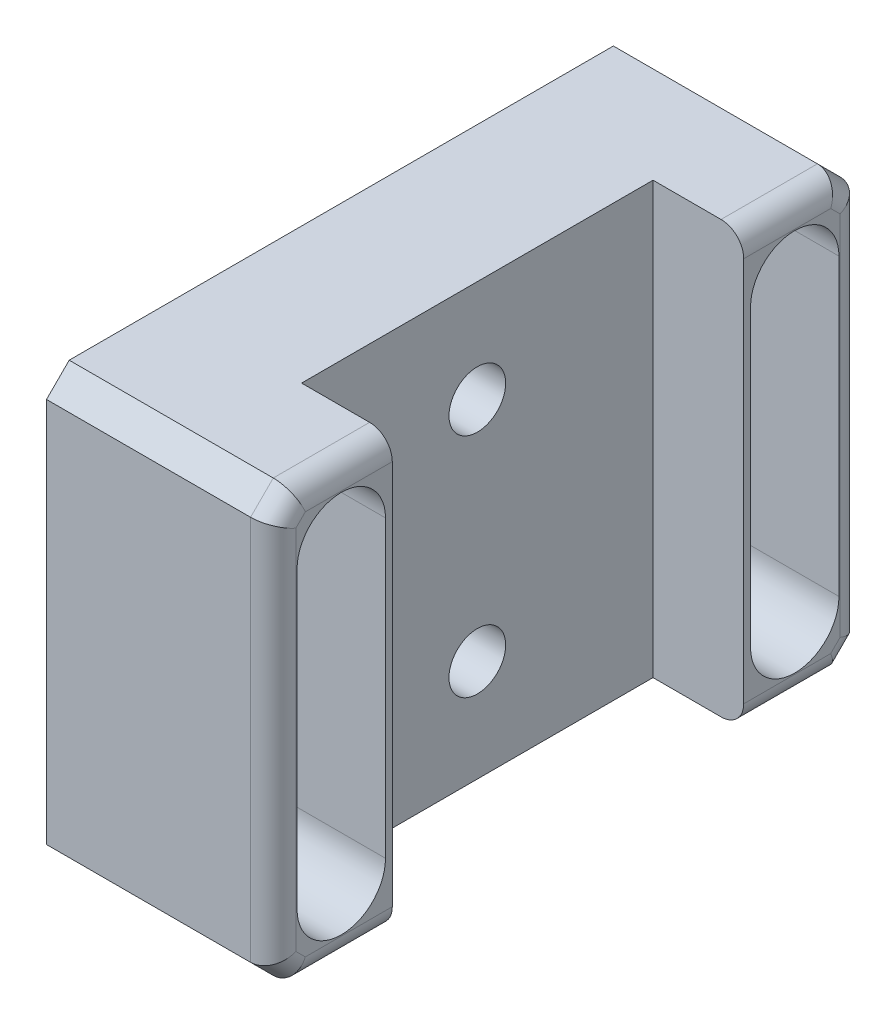
SolidWorks part; units mm, degrees
ref_plane "Спереди" through (0, 0, 0) normal (0, 0, 1) x (1, 0, 0)
ref_plane "Сверху" through (0, 0, 0) normal (0, 1, 0) x (1, 0, 0)
ref_plane "Справа" through (0, 0, 0) normal (1, 0, 0) x (0, 0, -1)
sketch "Эскиз1" plane through (0, 0, 0) normal (1, 0, 0) x (0, 0, -1)
  line L0 (-10, 6.5) -> (-10, -6.5) construction
  line L1 (-13, 9.5) -> (13, 9.5)
  line L2 (-13, 9.5) -> (-13, -9.5)
  line L3 (-13, -9.5) -> (13, -9.5)
  line L4 (13, 9.5) -> (13, -9.5)
  line L5 (-13, 9.5) -> (13, -9.5) construction
  line L6 (-13, -9.5) -> (13, 9.5) construction
  line L7 (-8.75, 6.5) -> (-8.75, -6.5)
  line L8 (-11.25, 6.5) -> (-11.25, -6.5)
  line L9 (0, 9.5) -> (0, -9.5) construction
  line L10 (10, 6.5) -> (10, -6.5) construction
  line L11 (8.75, 6.5) -> (8.75, -6.5)
  line L12 (11.25, 6.5) -> (11.25, -6.5)
  arc A0 (-8.75, 6.5) -> (-11.25, 6.5) centre (-10, 6.5) ccw
  arc A1 (-11.25, -6.5) -> (-8.75, -6.5) centre (-10, -6.5) ccw
  arc A2 (8.75, 6.5) -> (11.25, 6.5) centre (10, 6.5) cw
  arc A3 (11.25, -6.5) -> (8.75, -6.5) centre (10, -6.5) cw
  point P0 (0, 0)
  point P8 (-10, 0)
  point P17 (10, 0)
  dimension "D1" = 26
  dimension "D2" = 2.5
  dimension "D3" = 20
  dimension "D5" = 3
  dimension "D4" = 19
extrude "Бобышка-Вытянуть1" add sketch "Эскиз1" along normal blind 10
sketch "Эскиз2" plane through (10, 0, 0) normal (1, 0, 0) x (0, 0, -1)
  line L0 (-13, -9.5) -> (13, -9.5) construction
  line L1 (7.75, 9.5) -> (-7.75, 9.5)
  line L2 (7.75, 9.5) -> (7.75, -9.5)
  line L3 (7.75, -9.5) -> (-7.75, -9.5)
  line L4 (-7.75, 9.5) -> (-7.75, -9.5)
  line L5 (7.75, 9.5) -> (-7.75, -9.5) construction
  line L6 (7.75, -9.5) -> (-7.75, 9.5) construction
  point P0 (0, 0)
  dimension "D1" = 15.5
extrude "Вырез-Вытянуть1" cut sketch "Эскиз2" against normal blind 4
sketch "Эскиз3" plane through (10, 0, 0) normal (1, 0, 0) x (0, 0, -1)
  line L0 (-10, -6.5) -> (-10, 6.5) construction
  line L1 (-11.95, -6.5) -> (-11.95, 6.5)
  line L2 (-8.05, -6.5) -> (-8.05, 6.5)
  line L3 (0, 9.5) -> (0, -9.5) construction
  line L4 (7.75, 9.5) -> (-7.75, 9.5) construction
  line L5 (-7.75, -9.5) -> (7.75, -9.5) construction
  line L6 (10, -6.5) -> (10, 6.5) construction
  line L7 (11.95, -6.5) -> (11.95, 6.5)
  line L8 (8.05, -6.5) -> (8.05, 6.5)
  arc A0 (-11.95, -6.5) -> (-8.05, -6.5) centre (-10, -6.5) ccw
  arc A1 (-8.05, 6.5) -> (-11.95, 6.5) centre (-10, 6.5) ccw
  arc A2 (-11.25, -6.5) -> (-8.75, -6.5) centre (-10, -6.5) ccw construction
  arc A3 (-8.75, 6.5) -> (-11.25, 6.5) centre (-10, 6.5) ccw construction
  arc A4 (11.95, -6.5) -> (8.05, -6.5) centre (10, -6.5) cw
  arc A5 (8.05, 6.5) -> (11.95, 6.5) centre (10, 6.5) cw
  point P2 (-10, 0)
  point P23 (10, 0)
  dimension "D1" = 3.9
extrude "Вырез-Вытянуть2" cut sketch "Эскиз3" against normal blind 4
chamfer "Фаска1" distance 1 angle 45 4 edges at (5, 9.5, -13) (5, -9.5, -13) (5, -9.5, 13) (5, 9.5, 13)
fillet "Скругление1" radius 1 10 edges at (10, 9, 12.5) (10, -9, 12.5) (10, -9, -12.5) (10, -9.5, -9.875) (10, 0, -13) (10, 9, -12.5) (10, 9.5, -9.875) (10, -9.5, 9.875) (10, 9.5, 9.875) (10, 0, 13)
sketch "Эскиз4" plane through (6, 0, 0) normal (1, 0, 0) x (0, 0, -1)
  line L0 (0, 9.5) -> (0, -9.5) construction
  line L1 (7.75, 9.5) -> (-7.75, 9.5) construction
  line L2 (-7.75, -9.5) -> (7.75, -9.5) construction
  line L3 (-7.75, 0) -> (7.75, 0) construction
  line L4 (-7.75, 9.5) -> (-7.75, -9.5) construction
  line L5 (7.75, -9.5) -> (7.75, 9.5) construction
  circle A0 centre (0, 5) radius 1.25
  circle A1 centre (0, -5) radius 1.25
  dimension "D1" = 2.5
  dimension "D2" = 10
extrude "Вырез-Вытянуть3" cut sketch "Эскиз4" against normal through all
sketch "Эскиз5" plane through (0, 0, 0) normal (-1, 0, 0) x (0, 0, 1)
  line L1 (1.1691, 2.975) -> (2.3383, 5)
  line L2 (2.3383, 5) -> (1.1691, 7.025)
  line L3 (1.1691, 7.025) -> (-1.1691, 7.025)
  line L4 (-1.1691, 7.025) -> (-2.3383, 5)
  line L5 (-2.3383, 5) -> (-1.1691, 2.975)
  line L6 (-1.1691, 2.975) -> (1.1691, 2.975)
  line L7 (1.1691, -7.025) -> (2.3383, -5)
  line L8 (2.3383, -5) -> (1.1691, -2.975)
  line L9 (1.1691, -2.975) -> (-1.1691, -2.975)
  line L10 (-1.1691, -2.975) -> (-2.3383, -5)
  line L11 (-2.3383, -5) -> (-1.1691, -7.025)
  line L12 (-1.1691, -7.025) -> (1.1691, -7.025)
  circle A0 centre (0, 5) radius 2.025 construction
  circle A1 centre (0, -5) radius 2.025 construction
  dimension "D1" = 4.05
  dimension "D2" = 4.05
extrude "Вырез-Вытянуть4" cut sketch "Эскиз5" against normal blind 2
equation "\"motor_diameter\"= 30"
equation "\"mm_diameter\"= IIF ( \"motor_diameter\" < 34 , 41 , \"motor_diameter\" + 8 )"
equation "\"upper_shafts_diameter\"= 5"
equation "\"upper_shats_length\"= 180"
equation "\"upper_bearing_d1\"= 10"
equation "\"upper_bearing_d2\"= 5"
equation "\"upper_bearing_h\"= 15"
equation "\"lower_shafts_diameter\"= 5"
equation "\"lower_shafts_length\"= 180"
equation "\"lower_bearing_d1\"= 10"
equation "\"lower_bearing_d2\"= 5"
equation "\"lower_bearing_h\"= 15"
equation "\"print_offset\"= 0.5"
equation "\"bh_screws_d\"= 2"
equation "\"bh_screws_h\"= 20"
equation "\"bh_screws_hh_d\"= 3.4"
equation "\"bh_screws_hh_h\"= 2"
equation "\"bh_nut_d\"= 3.8"
equation "\"bh_nut_h\"= 2"
equation "\"motor_screws_d\"= 3"
equation "\"motor_screws_h\"= 16"
equation "\"motor_screws_hh_d\"= 5.5"
equation "\"motor_screws_hh_h\"= 3"
equation "\"plate_hole_distance\"= 25.4"
equation "\"plate_screws_d\"= 6.5"
equation "\"shafts_diameter\"= IIF ( \"mm_diameter\" < 42 , 42 + 8 , \"mm_diameter\" + 8 )"
equation "\"central_hole_diameter\"= 8"
equation "\"bh_thikness\"= 4"
equation "\"ends_screws_d\"= 4"
equation "\"ends_screws_h\"= 16"
equation "\"ends_screws_hh_d\"= 6.7"
equation "\"ends_screws_hh_h\"= 4.1"
equation "\"ends_nut_d\"= 6.8"
equation "\"ends_nut_h\"= 3"
equation "\"system_radius\" = ( \"shafts_diameter\" + 12 + \"bh_thikness\" / 2 ) / 2"
equation "\"encoder_distance\"= \"system_radius\" + 4"
equation "\"tape_position\"= \"encoder_distance\" - 2 + 3.9 + 1.7 / 2"
equation "\"D2@Эскиз1\"=\"bh_screws_d\"+\"print_offset\""
equation "\"D1@Бобышка-Вытянуть1\"=6"
equation "\"D4@Эскиз1\"=\"upper_bearing_h\" + 6 + 3 - 8 + 3"
equation "\"D1@Эскиз2\"=\"print_offset\"+15"
equation "\"D1@Эскиз3\"=\"bh_screws_hh_d\"+\"print_offset\""
equation "\"D1@Вырез-Вытянуть2\"=\"bh_screws_hh_h\"+2"
equation "\"D1@Эскиз4\"=\"bh_screws_d\"+\"print_offset\""
equation "\"D1@Эскиз5\"=\"bh_nut_d\"+\"print_offset\"/2"
equation "\"D2@Эскиз5\"=\"D1@Эскиз5\""
equation "\"D1@Вырез-Вытянуть4\"=\"bh_nut_h\""
